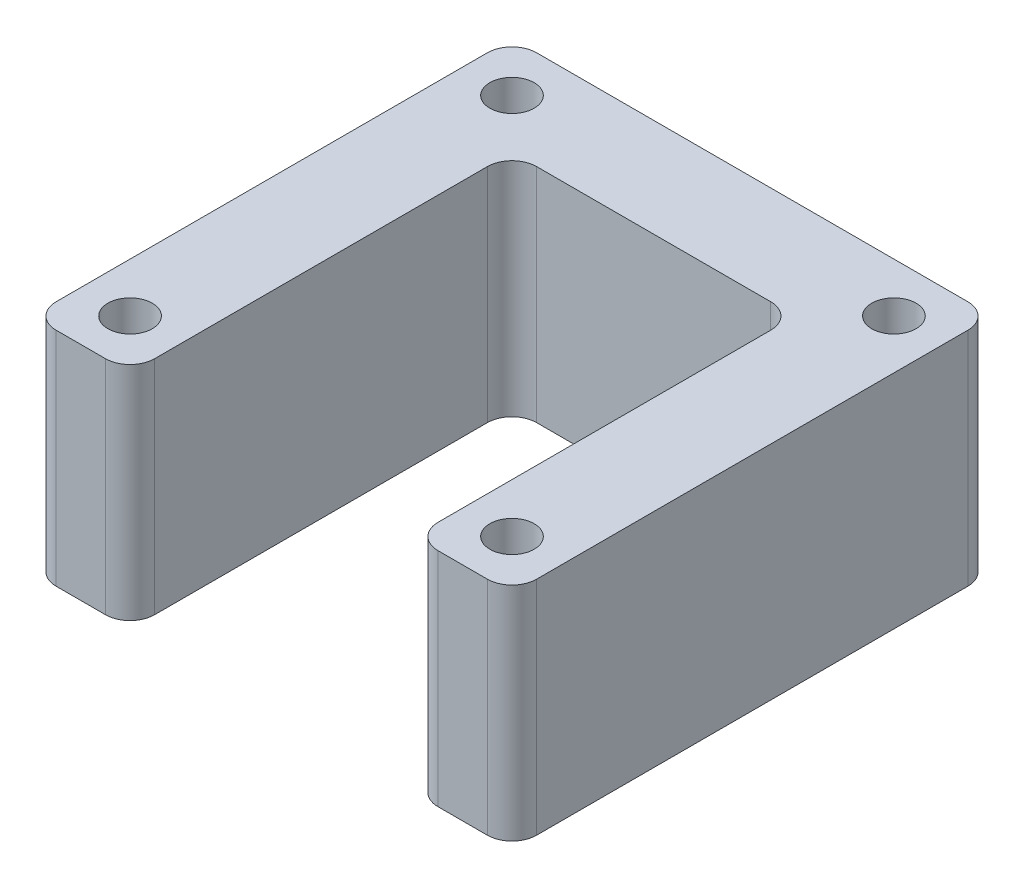
SolidWorks part; units mm, degrees
ref_plane "Front Plane" through (0, 0, 0) normal (0, 0, 1) x (1, 0, 0)
ref_plane "Top Plane" through (0, 0, 0) normal (0, 1, 0) x (1, 0, 0)
ref_plane "Right Plane" through (0, 0, 0) normal (1, 0, 0) x (0, 0, -1)
sketch "Sketch1" plane through (0, 0, 0) normal (0, 1, 0) x (1, 0, 0)
  line L0 (-15.6074, 23.2629) -> (23.3926, 23.2629)
  line L1 (-17.2574, 24.9129) -> (25.0426, 24.9129)
  line L2 (-17.2574, 24.9129) -> (-17.2574, -17.3871)
  line L3 (-17.2574, -17.3871) -> (25.0426, -17.3871)
  line L4 (25.0426, 24.9129) -> (25.0426, -17.3871)
  line L5 (23.3926, 23.2629) -> (23.3926, -15.7371)
  line L6 (23.3926, -15.7371) -> (15.3926, -15.7371)
  line L7 (15.3926, -15.7371) -> (15.3926, 15.2629)
  line L8 (15.3926, 15.2629) -> (-7.6074, 15.2629)
  line L9 (-7.6074, 15.2629) -> (-7.6074, -15.7371)
  line L10 (-15.6074, 23.2629) -> (-15.6074, -15.7371)
  line L11 (-15.6074, -15.7371) -> (-7.6074, -15.7371)
  circle A0 centre (-11.6074, 19.2629) radius 1.8
  circle A1 centre (19.3926, 19.2629) radius 1.8
  circle A2 centre (19.3926, -11.7371) radius 1.8
  circle A3 centre (-11.6074, -11.7371) radius 1.8
  dimension "D3" = 3.6
  dimension "D4" = 3.6
  dimension "D5" = 3.6
  dimension "D6" = 3.6
  dimension "D1" = 42.3
  dimension "D2" = 42.3
  dimension "D7" = 5.65
  dimension "D8" = 5.65
  dimension "D9" = 5.65
  dimension "D10" = 5.65
  dimension "D11" = 5.65
  dimension "D12" = 5.65
  dimension "D13" = 5.65
  dimension "D14" = 5.65
  dimension "D15" = 4
  dimension "D16" = 4
  dimension "D17" = 4
  dimension "D18" = 4
  dimension "D19" = 8
  dimension "D20" = 4
  dimension "D21" = 4
  dimension "D22" = 4
extrude "Boss-Extrude1" add sketch "Sketch1" along normal blind 18 contours L10 L11 L9 L8 L7 L6 L5 L0 A3 A2 A1 A0
fillet "Fillet1" radius 2 8 edges at (-15.6074, 9, -23.2629) (23.3926, 9, -23.2629) (-15.6074, 9, 15.7371) (-7.6074, 9, 15.7371) (-7.6074, 9, -15.2629) (15.3926, 9, -15.2629) (15.3926, 9, 15.7371) (23.3926, 9, 15.7371)
